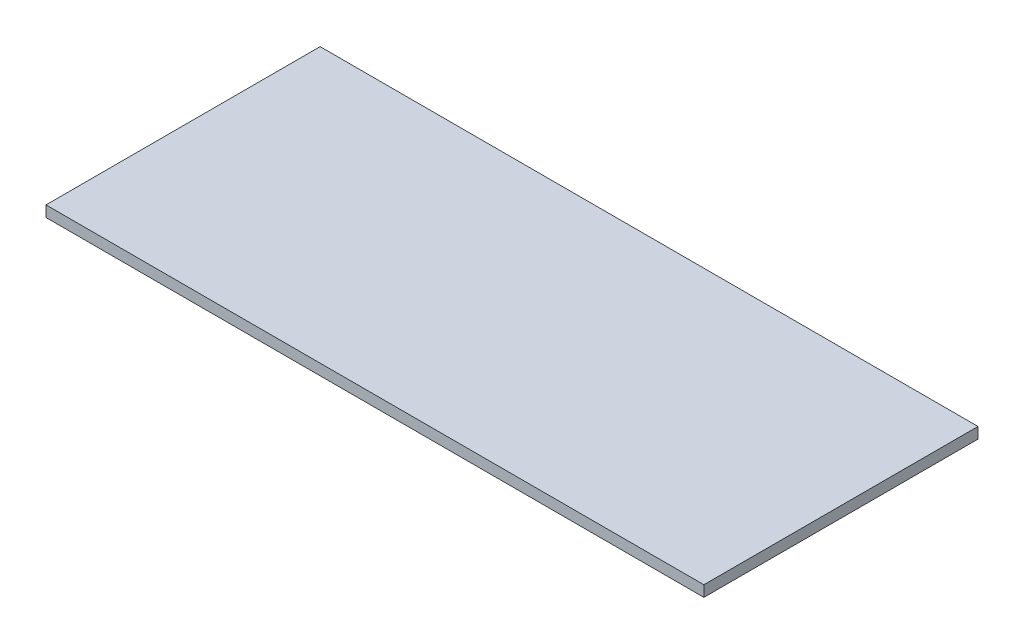
SolidWorks part; units mm, degrees
ref_plane "Front Plane" through (0, 0, 0) normal (0, 0, 1) x (1, 0, 0)
ref_plane "Top Plane" through (0, 0, 0) normal (0, 1, 0) x (1, 0, 0)
ref_plane "Right Plane" through (0, 0, 0) normal (1, 0, 0) x (0, 0, -1)
sketch "Sketch1" plane through (0, 0, 0) normal (0, 0, 1) x (1, 0, 0)
  line L1 (-240, -4) -> (240, -4)
  line L2 (-240, -4) -> (-240, 4)
  line L3 (-240, 4) -> (240, 4)
  line L4 (240, -4) -> (240, 4)
  line L5 (-240, -4) -> (240, 4) construction
  line L6 (-240, 4) -> (240, -4) construction
  point P0 (0, 0)
  dimension "D1" = 480
  dimension "D2" = 8
extrude "Boss-Extrude1" add sketch "Sketch1" along normal blind 200
